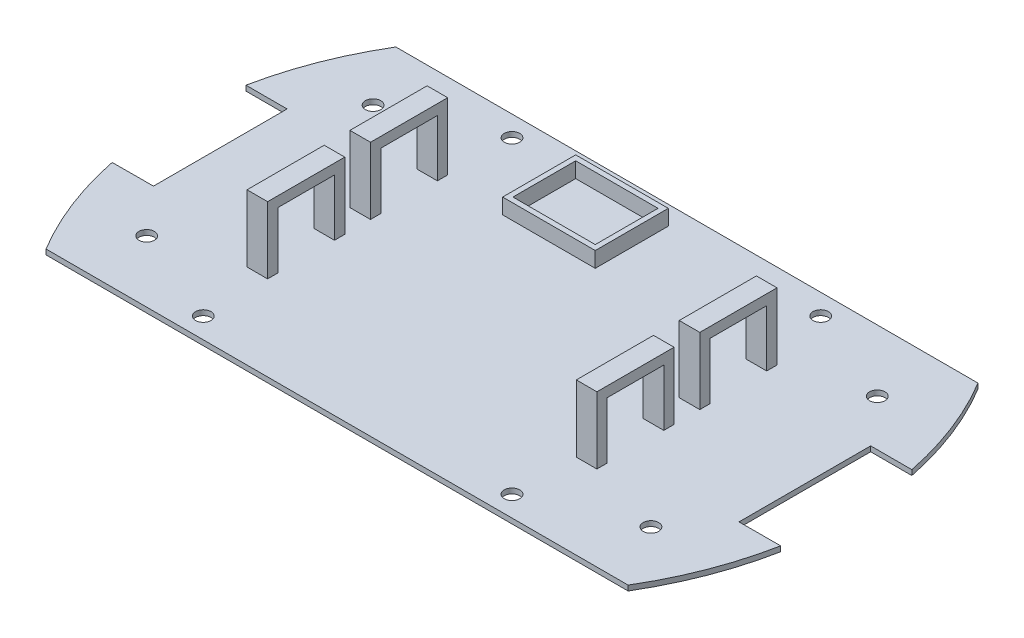
SolidWorks part; units mm, degrees
ref_plane "前基準面" through (0, 0, 0) normal (0, 0, 1) x (1, 0, 0)
ref_plane "上基準面" through (0, 0, 0) normal (0, 1, 0) x (1, 0, 0)
ref_plane "右基準面" through (0, 0, 0) normal (1, 0, 0) x (0, 0, -1)
sketch "草圖7" plane through (0, 0, 0) normal (0, 1, 0) x (1, 0, 0)
  line L1 (-34, 34) -> (34, 34)
  line L2 (-34, 34) -> (-34, -34)
  line L3 (-34, -34) -> (34, -34)
  line L4 (34, 34) -> (34, -34)
  line L5 (-34, 34) -> (34, -34) construction
  line L6 (-34, -34) -> (34, 34) construction
  point P0 (0, 0)
  point P7 (-30, 30)
  point P10 (30, 30)
  point P11 (30, -30)
  point P12 (-30, -30)
  point P13 (0, 0)
  dimension "D1" = 68
  dimension "D2" = 4
  dimension "D3" = 4
sketch "草圖10" plane through (0, 0, 0) normal (0, 1, 0) x (1, 0, 0)
  line L0 (-56.5685, 34) -> (56.5685, 34)
  line L1 (-34, 34) -> (34, 34) construction
  line L2 (-56.5685, -34) -> (56.5685, -34)
  line L3 (-34, -34) -> (34, -34) construction
  line L4 (-34, 34) -> (-34, -34) construction
  line L5 (0, 0) -> (0, 19.0172) construction
  line L6 (0, 0) -> (-12.2861, 0) construction
  line L7 (-56.707, 13) -> (-56.707, -13)
  line L8 (-64.707, 13) -> (64.707, 13)
  line L9 (56.707, 13) -> (56.707, -13)
  line L10 (-64.707, -13) -> (64.7924, -12.5675)
  arc A0 (-64.707, -13) -> (-56.5685, -34) centre (0, 0) ccw
  arc A3 (-56.5685, 34) -> (-64.707, 13) centre (0, 0) ccw
  arc A4 (64.707, 13) -> (56.5685, 34) centre (0, 0) ccw
  arc A5 (56.5685, -34) -> (64.7924, -12.5675) centre (0, 0) ccw
  point P12 (-49, 22)
  point P24 (56.707, 0)
  point P27 (-56.707, 0)
  dimension "D1" = 8
  dimension "D2" = 13
  dimension "D4" = 15
  dimension "D5" = 12
extrude "填料-伸長2" add sketch "草圖10" along normal blind 1
hole_wizard "Ø3.0mm 定位孔1" positions "3D草圖2" profile "草圖13" hole size "Ø3.0" standard "JIS"
sketch3d "3D草圖2"
  point P0 (-30, 0, -30)
  point P3 (-30, 1, -30)
  point P5 (-30, 1, 30)
  point P11 (30, 1, -30)
  point P13 (30, 1, 30)
sketch "草圖13" plane through (30, 1, 30) normal (1, 0, 0) x (0, 0, 1)
  line L0 (0, 0) -> (0, 4.9013)
  line L1 (0, 4.9013) -> (1.5, 4)
  line L2 (1.5, 4) -> (1.5, 0)
  line L5 (1.5, 0) -> (0, 0)
  line L10 (0, 4.9013) -> (-1.5, 4) construction
  line L11 (0, -6.35) -> (0, 107.95) construction
  dimension "鑽孔直徑" = 3
  dimension "鑽孔深度" = 4
  dimension "導頭角度" = 118
hole_wizard "Ø3.0mm 定位孔2" positions "3D草圖3" profile "草圖14" hole size "Ø3.0" standard "JIS"
sketch3d "3D草圖3"
  point P0 (-49, 1, -22)
sketch "草圖14" plane through (-49, 1, -22) normal (1, 0, 0) x (0, 0, 1)
  line L0 (0, 0) -> (0, 4.9013)
  line L1 (0, 4.9013) -> (1.5, 4)
  line L2 (1.5, 4) -> (1.5, 0)
  line L5 (1.5, 0) -> (0, 0)
  line L10 (0, 4.9013) -> (-1.5, 4) construction
  line L11 (0, -6.35) -> (0, 107.95) construction
  dimension "鑽孔直徑" = 3
  dimension "鑽孔深度" = 4
  dimension "導頭角度" = 118
pattern_linear "直線複製排列1" count 2 spacing 98 along (1, 0, 0) count 2 spacing 44 along (0, 0, 1) of "Ø3.0mm 定位孔2"
sketch "草圖15" plane through (0, 1, 0) normal (0, 1, 0) x (1, 0, 0)
  line L1 (-64.6001, 5.5) -> (55.3999, 5.5)
  line L2 (-64.6001, 5.5) -> (-64.6001, -5.5)
  line L3 (-64.6001, -5.5) -> (55.3999, -5.5)
  line L4 (55.3999, 5.5) -> (55.3999, -5.5)
  line L5 (-64.6001, 5.5) -> (55.3999, -5.5) construction
  line L6 (-64.6001, -5.5) -> (55.3999, 5.5) construction
  point P0 (-4.6001, 0)
  dimension "D1" = 11
  dimension "D2" = 120
sketch "草圖16" plane through (0, 1, 0) normal (0, 1, 0) x (1, 0, 0)
  line L0 (0, 0) -> (-16.1406, 0) construction
  line L1 (-34, 17.5) -> (-30, 17.5)
  line L2 (-34, 17.5) -> (-34, 2.5)
  line L3 (-34, 2.5) -> (-30, 2.5)
  line L4 (-30, 17.5) -> (-30, 2.5)
  line L5 (-34, 17.5) -> (-30, 2.5) construction
  line L6 (-34, 2.5) -> (-30, 17.5) construction
  line L7 (34, -17.5) -> (30, -2.5) construction
  line L8 (0, 10) -> (0, 20.5838) construction
  line L9 (34, 2.5) -> (30, 17.5) construction
  line L10 (34, 17.5) -> (30, 2.5) construction
  line L11 (30, 17.5) -> (30, 2.5)
  line L12 (34, 2.5) -> (30, 2.5)
  line L13 (34, 17.5) -> (34, 2.5)
  line L14 (34, 17.5) -> (30, 17.5)
  line L15 (34, -2.5) -> (30, -17.5) construction
  line L16 (0, -10) -> (0, -20.5838) construction
  line L17 (-34, -2.5) -> (-30, -17.5) construction
  line L18 (-34, -17.5) -> (-30, -2.5) construction
  line L19 (34, -17.5) -> (30, -17.5)
  line L20 (34, -17.5) -> (34, -2.5)
  line L21 (34, -2.5) -> (30, -2.5)
  line L22 (30, -17.5) -> (30, -2.5)
  line L23 (-30, -17.5) -> (-30, -2.5)
  line L24 (-34, -2.5) -> (-30, -2.5)
  line L25 (-34, -17.5) -> (-34, -2.5)
  line L26 (-34, -17.5) -> (-30, -17.5)
  point P0 (-32, 10)
  point P14 (32, 10)
  point P25 (32, -10)
  point P26 (-32, -10)
  dimension "D1" = 4
  dimension "D2" = 15
extrude "填料-伸長3" add sketch "草圖16" along normal blind 13
sketch "草圖17" plane through (-34, 0, 0) normal (-1, 0, 0) x (0, 0, 1)
  line L0 (-5.5, 1) -> (5.5, 1) construction
  line L1 (-15.5, 12) -> (-4.5, 12)
  line L2 (-15.5, 12) -> (-15.5, 1)
  line L3 (-15.5, 1) -> (-4.5, 1)
  line L4 (-4.5, 12) -> (-4.5, 1)
  line L5 (-15.5, 12) -> (-4.5, 1) construction
  line L6 (-15.5, 1) -> (-4.5, 12) construction
  line L8 (-17.5, 14) -> (-2.5, 14) construction
  line L9 (4.5, 12) -> (15.5, 12)
  line L10 (4.5, 12) -> (4.5, 1)
  line L11 (4.5, 1) -> (15.5, 1)
  line L12 (15.5, 12) -> (15.5, 1)
  line L13 (4.5, 12) -> (15.5, 1) construction
  line L14 (4.5, 1) -> (15.5, 12) construction
  line L15 (34, 1) -> (13, 1) construction
  line L16 (2.5, 14) -> (17.5, 14) construction
  point P0 (-10, 6.5)
  point P9 (-10, 14)
  point P10 (10, 6.5)
  point P19 (10, 14)
  dimension "D1" = 11
  dimension "D2" = 11
  dimension "D3" = 11
sketch "草圖18" plane through (0, 1, 0) normal (0, 1, 0) x (1, 0, 0)
  line L1 (-16.938, 29.3173) -> (-0.938, 29.3173)
  line L2 (-16.938, 29.3173) -> (-16.938, 17.1173)
  line L3 (-16.938, 17.1173) -> (-0.938, 17.1173)
  line L4 (-0.938, 29.3173) -> (-0.938, 17.1173)
  line L5 (-16.938, 29.3173) -> (-0.938, 17.1173) construction
  line L6 (-16.938, 17.1173) -> (-0.938, 29.3173) construction
  line L7 (-17.938, 30.3173) -> (0.062, 30.3173)
  line L8 (-17.938, 30.3173) -> (-17.938, 16.1173)
  line L9 (-17.938, 16.1173) -> (0.062, 16.1173)
  line L10 (0.062, 30.3173) -> (0.062, 16.1173)
  line L11 (-17.938, 30.3173) -> (0.062, 16.1173) construction
  line L12 (-17.938, 16.1173) -> (0.062, 30.3173) construction
  point P0 (-8.938, 23.2173)
  point P5 (-8.938, 23.2173)
  dimension "D1" = 16
  dimension "D2" = 12.2
  dimension "D3" = 1
  dimension "D4" = 1
  dimension "D5" = 1
  dimension "D6" = 1
extrude "除料-伸長1" cut sketch "草圖17" against normal up to surface (68 mm away) up to face at (34, 7.5, -10)
extrude "填料-伸長4" add sketch "草圖18" along normal blind 3
sketch "草圖19" plane through (0, 1, 0) normal (0, 1, 0) x (1, 0, 0)
  line L1 (-105.3663, 66.0318) -> (-51.3663, 66.0318)
  line L2 (-105.3663, 66.0318) -> (-105.3663, -32.9682)
  line L3 (-105.3663, -32.9682) -> (-51.3663, -32.9682)
  line L4 (-51.3663, 66.0318) -> (-51.3663, -32.9682)
  line L5 (-105.3663, 66.0318) -> (-51.3663, -32.9682) construction
  line L6 (-105.3663, -32.9682) -> (-51.3663, 66.0318) construction
  point P0 (-78.3663, 16.5318)
  dimension "D1" = 54
  dimension "D2" = 99
